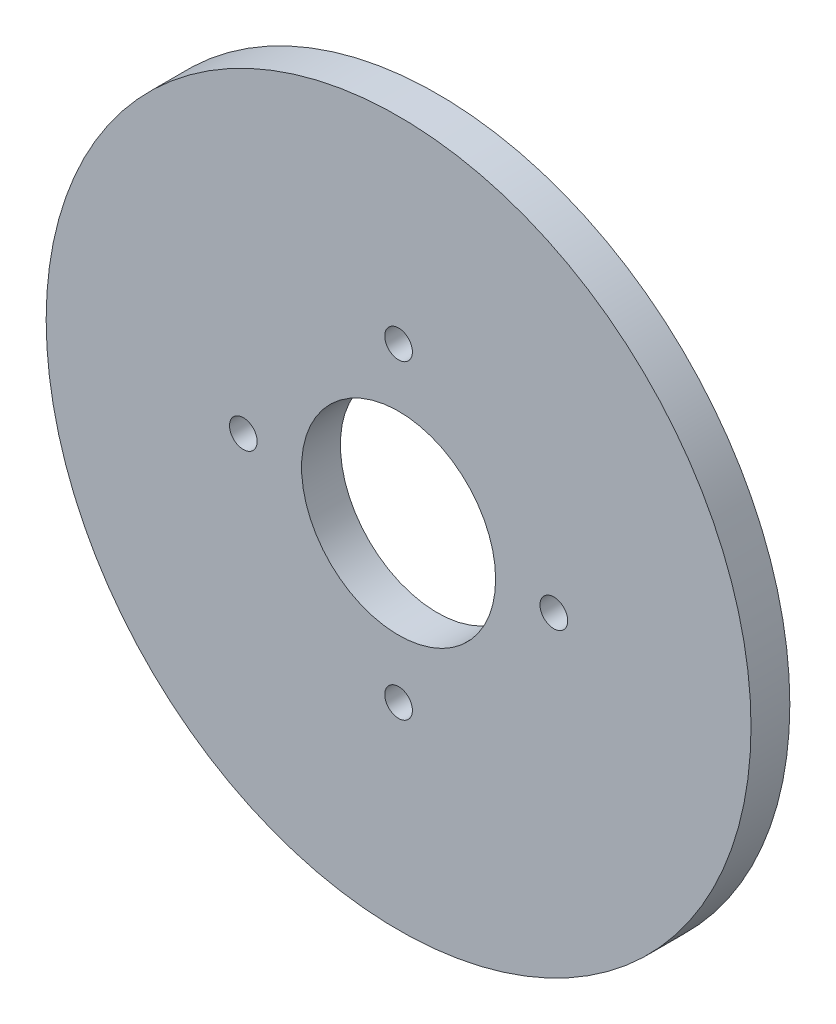
SolidWorks part; units mm, degrees
material "6061 Alloy"
ref_plane "Front Plane" through (0, 0, 0) normal (0, 0, 1) x (1, 0, 0)
ref_plane "Top Plane" through (0, 0, 0) normal (0, 1, 0) x (1, 0, 0)
ref_plane "Right Plane" through (0, 0, 0) normal (1, 0, 0) x (0, 0, -1)
sketch "Sketch1" plane through (0, 0, 0) normal (0, 0, 1) x (1, 0, 0)
  circle A0 centre (0, 0) radius 28.829
  circle A1 centre (0, 0) radius 7.9375
  dimension "D1" = 57.658
  dimension "D2" = 15.875
extrude "Boss-Extrude1" add sketch "Sketch1" along normal blind 3.175
hole_wizard "Tap Drill for #4-40 Tap1" positions "Sketch2" profile "Sketch3" hole size "#4-40" standard "ANSI Inch"
sketch "Sketch2" plane through (0, 0, 3.175) normal (0, 0, 1) x (1, 0, 0)
  point P0 (0, 12.7)
  point P2 (0, -12.7)
  point P4 (12.7, 0)
  point P6 (-12.7, 0)
  dimension "D1" = 12.7
  dimension "D2" = 12.7
  dimension "D3" = 12.7
  dimension "D4" = 12.7
sketch "Sketch3" plane through (0, 12.7, 3.175) normal (1, 0, 0) x (0, -1, 0)
  line L0 (0, 0) -> (0, 4.6792)
  line L1 (0, 4.6792) -> (1.1303, 4)
  line L2 (1.1303, 4) -> (1.1303, 0)
  line L5 (1.1303, 0) -> (0, 0)
  line L10 (0, 4.6792) -> (-1.1303, 4) construction
  line L11 (0, -6.35) -> (0, 107.95) construction
  dimension "Hole Dia." = 2.2606
  dimension "Hole Depth" = 4
  dimension "Drill Angle" = 118
